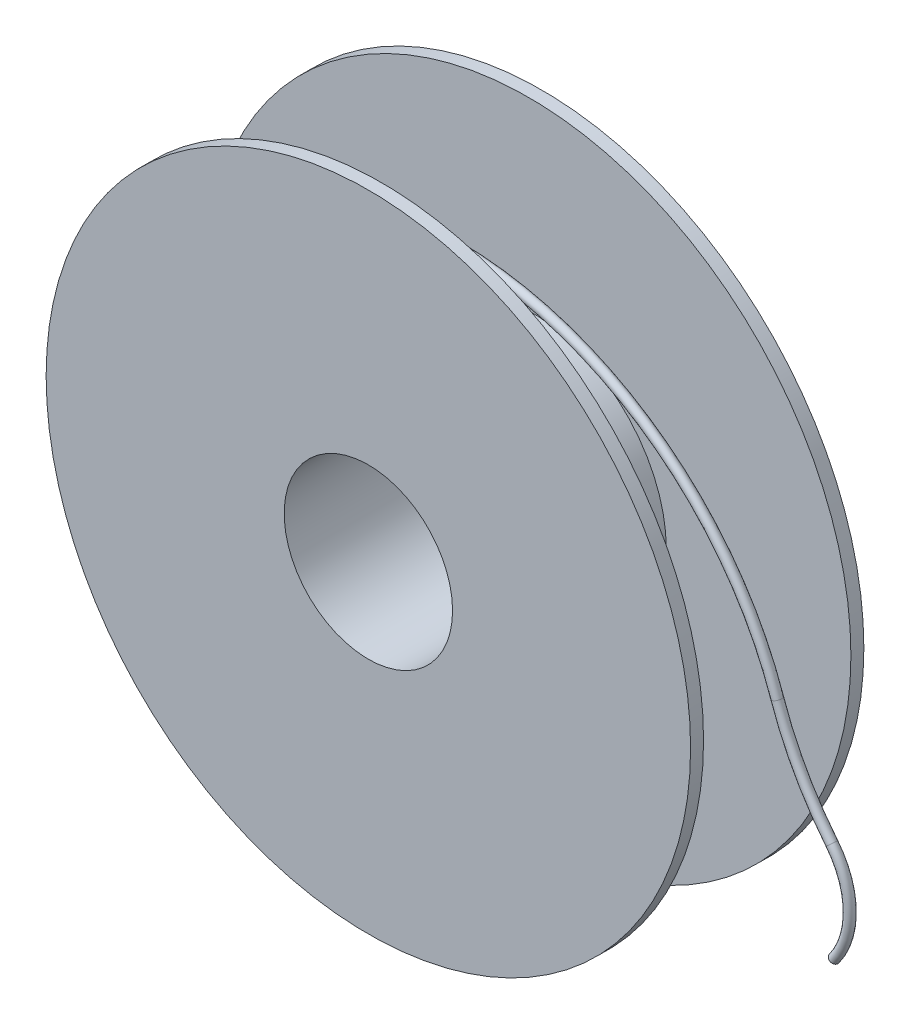
SolidWorks part; units mm, degrees
ref_plane "Plan de face" through (0, 0, 0) normal (0, 0, 1) x (1, 0, 0)
ref_plane "Plan de dessus" through (0, 0, 0) normal (0, 1, 0) x (1, 0, 0)
ref_plane "Plan de droite" through (0, 0, 0) normal (1, 0, 0) x (0, 0, -1)
sketch "Esquisse1" plane through (0, 0, 0) normal (0, 1, 0) x (1, 0, 0)
  line L0 (0, 0) -> (0, 26.75) construction
  line L5 (26, -26.75) -> (99.5, -26.75)
  line L6 (26, -26.75) -> (26, 26.75)
  line L7 (26, 26.75) -> (99.5, 26.75)
  line L8 (99.5, -26.75) -> (99.5, -22.75)
  line L9 (99.5, 22.75) -> (42.5, 22.75)
  line L10 (42.5, 22.75) -> (42.5, -22.75)
  line L11 (42.5, -22.75) -> (99.5, -22.75)
  line L12 (26, 0) -> (99.5, 0) construction
  line L13 (99.5, 22.75) -> (99.5, 26.75)
  point P5 (26, 0)
  point P14 (0, 0)
  dimension "D1" = 99.5
  dimension "D2" = 26
  dimension "D3" = 53.5
  dimension "D4" = 4
  dimension "D5" = 85
revolve "Révolution1" add sketch "Esquisse1" angle 360 about L0
sketch "Esquisse2" plane through (0, 0, 0) normal (0, 0, 1) x (1, 0, 0)
  line L0 (0, 99.5) -> (0, 42.5) construction
  line L1 (0, 71) -> (-69.7083, 71) construction
  line L2 (99.5, 0) -> (194.0637, 32.5224) construction
  line L3 (194.0637, 32.5224) -> (116.3262, -30.3814) construction
  line L4 (116.3262, -30.3814) -> (96.8918, -46.1073) construction
  line L5 (96.8918, -46.1073) -> (117.1119, -60.8093) construction
  arc A0 (-42.5, 0) -> (-56.75, 14.25) centre (-42.5, 14.25) cw
  circle A1 centre (0, 0) radius 42.5 construction
  circle A2 centre (0, 0) radius 99.5 construction
  arc A3 (-56.75, 14.25) -> (0, 71) centre (0, 14.25) cw
  arc A4 (0, 71) -> (99.5, 0) centre (0, -34.2201) cw
  arc A5 (99.5, 0) -> (116.3262, -30.3814) centre (194.0637, 32.5224) ccw
  arc A6 (116.3262, -30.3814) -> (117.1119, -60.8093) centre (96.8918, -46.1073) cw
  dimension "D2" = 100
  dimension "D4" = 25
  dimension "D1" = 20
  dimension "D3" = 75
ref_plane "Plan1" through (-42.5, 0, 0) normal (-1, 0, 0) x (0, 0, 1)
sketch "Esquisse3" plane through (-42.5, 0, 0) normal (-1, 0, 0) x (0, 0, 1)
  circle A0 centre (0, 0) radius 1.425
  dimension "D1" = 2.85
sweep "Balayage1" add profiles "Esquisse3" path "Esquisse2"
